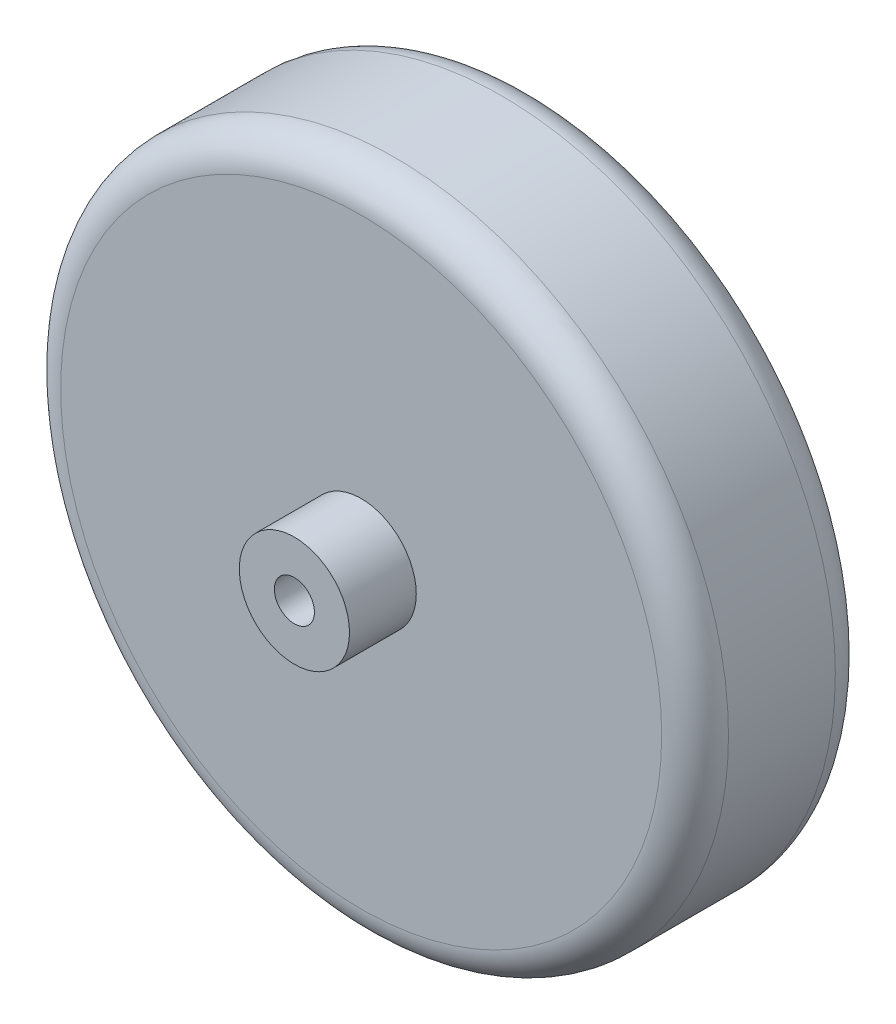
SolidWorks part; units mm, degrees
ref_plane "Front Plane" through (0, 0, 0) normal (0, 0, 1) x (1, 0, 0)
ref_plane "Top Plane" through (0, 0, 0) normal (0, 1, 0) x (1, 0, 0)
ref_plane "Right Plane" through (0, 0, 0) normal (1, 0, 0) x (0, 0, -1)
sketch "Sketch1" plane through (0, 0, 0) normal (0, 0, 1) x (1, 0, 0)
  circle A0 centre (0, 0) radius 50
  circle A1 centre (0, 0) radius 3
  dimension "D1" = 100
  dimension "D2" = 6
extrude "Boss-Extrude1" add sketch "Sketch1" along normal blind 26
fillet "Fillet2" radius 5 2 edges at (50, 0, 0) (50, 0, 26)
sketch "Sketch3" plane through (0, 0, 26) normal (0, 0, 1) x (1, 0, 0)
  circle A0 centre (0, 0) radius 8.2486
extrude "Boss-Extrude2" add sketch "Sketch3" along normal blind 10
sketch "Sketch4" plane through (0, 0, 36) normal (0, 0, 1) x (1, 0, 0)
  circle A0 centre (0, 0) radius 3
  dimension "D1" = 6
extrude "Cut-Extrude1" cut sketch "Sketch4" against normal blind 26
